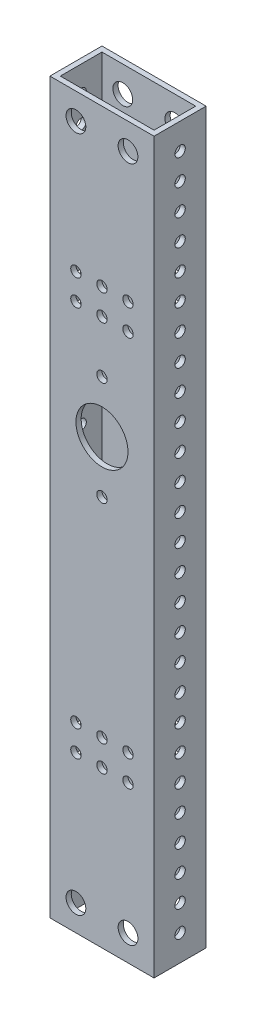
SolidWorks part; units mm, degrees
ref_plane "Front Plane" through (0, 0, 0) normal (0, 0, 1) x (1, 0, 0)
ref_plane "Top Plane" through (0, 0, 0) normal (0, 1, 0) x (1, 0, 0)
ref_plane "Right Plane" through (0, 0, 0) normal (1, 0, 0) x (0, 0, -1)
sketch "Sketch1" plane through (0, 0, 0) normal (0, 1, 0) x (1, 0, 0)
  line L1 (-48.4215, 22.2526) -> (2.3785, 22.2526)
  line L2 (-48.4215, 22.2526) -> (-48.4215, -3.1474)
  line L3 (-48.4215, -3.1474) -> (2.3785, -3.1474)
  line L4 (2.3785, 22.2526) -> (2.3785, -3.1474)
  line L5 (-48.4215, 22.2526) -> (2.3785, -3.1474) construction
  line L6 (-48.4215, -3.1474) -> (2.3785, 22.2526) construction
  line L7 (-45.8815, 19.7126) -> (-0.1615, 19.7126)
  line L8 (-45.8815, 19.7126) -> (-45.8815, -0.6074)
  line L9 (-45.8815, -0.6074) -> (-0.1615, -0.6074)
  line L10 (-0.1615, 19.7126) -> (-0.1615, -0.6074)
  line L11 (-45.8815, 19.7126) -> (-0.1615, -0.6074) construction
  line L12 (-45.8815, -0.6074) -> (-0.1615, 19.7126) construction
  point P0 (-23.0215, 9.5526)
  point P5 (-48.4215, 9.5526)
  point P6 (-23.0215, 9.5526)
  dimension "D1" = 50.8
  dimension "D2" = 25.4
  dimension "D3" = 2.54
  dimension "D4" = 2.54
extrude "Boss-Extrude1" add sketch "Sketch1" along normal blind 355.6
sketch "Sketch2" plane through (2.3785, 0, 0) normal (1, 0, 0) x (0, 0, -1)
  line L0 (-3.1474, 355.6) -> (-3.1474, 0) construction
  line L1 (-3.1474, 355.6) -> (22.2526, 355.6) construction
  circle A0 centre (9.5526, 342.9) radius 2.54
  circle A1 centre (9.5526, 330.2) radius 2.54
  circle A2 centre (9.5526, 317.5) radius 2.54
  circle A3 centre (9.5526, 304.8) radius 2.54
  circle A4 centre (9.5526, 292.1) radius 2.54
  circle A5 centre (9.5526, 279.4) radius 2.54
  circle A6 centre (9.5526, 266.7) radius 2.54
  circle A7 centre (9.5526, 254) radius 2.54
  circle A8 centre (9.5526, 241.3) radius 2.54
  circle A9 centre (9.5526, 228.6) radius 2.54
  circle A10 centre (9.5526, 215.9) radius 2.54
  circle A11 centre (9.5526, 203.2) radius 2.54
  circle A12 centre (9.5526, 190.5) radius 2.54
  circle A13 centre (9.5526, 177.8) radius 2.54
  circle A14 centre (9.5526, 165.1) radius 2.54
  circle A15 centre (9.5526, 152.4) radius 2.54
  circle A16 centre (9.5526, 139.7) radius 2.54
  circle A17 centre (9.5526, 127) radius 2.54
  circle A18 centre (9.5526, 114.3) radius 2.54
  circle A19 centre (9.5526, 101.6) radius 2.54
  circle A20 centre (9.5526, 88.9) radius 2.54
  circle A21 centre (9.5526, 76.2) radius 2.54
  circle A22 centre (9.5526, 63.5) radius 2.54
  circle A23 centre (9.5526, 50.8) radius 2.54
  circle A24 centre (9.5526, 38.1) radius 2.54
  circle A25 centre (9.5526, 25.4) radius 2.54
  circle A26 centre (9.5526, 12.7) radius 2.54
  dimension "D4" = 5.08
  dimension "D1" = 12.7
  dimension "D2" = 12.7
  dimension "D3" = 27
extrude "Cut-Extrude2" cut sketch "Sketch2" against normal blind 355.6
sketch "Sketch3" plane through (0, 0, -22.2526) normal (0, 0, -1) x (-1, 0, 0)
  line L0 (-2.3785, 355.6) -> (48.4215, 355.6) construction
  line L1 (48.4215, 355.6) -> (48.4215, 0) construction
  line L2 (-2.3785, 355.6) -> (-2.3785, 0) construction
  line L3 (-2.3785, 215.9) -> (48.4215, 215.9) construction
  line L4 (-2.3785, 177.8) -> (48.4215, 177.8) construction
  circle A0 centre (10.3215, 342.9) radius 4.826
  circle A1 centre (35.7215, 342.9) radius 4.826
  circle A2 centre (10.3215, 279.4) radius 2.54
  circle A3 centre (23.0215, 279.4) radius 2.54
  circle A4 centre (35.7215, 279.4) radius 2.54
  circle A5 centre (10.3215, 266.7) radius 2.54
  circle A6 centre (23.0215, 266.7) radius 2.54
  circle A7 centre (35.7215, 266.7) radius 2.54
  circle A8 centre (23.0215, 241.3) radius 2.54
  circle A9 centre (23.0215, 215.9) radius 12.7
  circle A10 centre (23.0215, 190.5) radius 2.54
  circle A11 centre (35.7215, 88.9) radius 2.54
  circle A12 centre (23.0215, 88.9) radius 2.54
  circle A13 centre (10.3215, 88.9) radius 2.54
  circle A14 centre (10.3215, 76.2) radius 2.54
  circle A15 centre (23.0215, 76.2) radius 2.54
  circle A16 centre (35.7215, 76.2) radius 2.54
  circle A17 centre (35.7215, 12.7) radius 4.826
  circle A18 centre (10.3215, 12.7) radius 4.826
  dimension "D1" = 9.652
  dimension "D2" = 9.652
  dimension "D8" = 5.08
  dimension "D13" = 5.08
  dimension "D14" = 25.4
  dimension "D3" = 12.7
  dimension "D4" = 12.7
  dimension "D5" = 12.7
  dimension "D6" = 12.7
  dimension "D7" = 63.5
  dimension "D9" = 12.7
  dimension "D12" = 25.4
  dimension "D15" = 25.4
  dimension "D10" = 3
  dimension "D11" = 2
extrude "Cut-Extrude3" cut sketch "Sketch3" against normal blind 355.6
